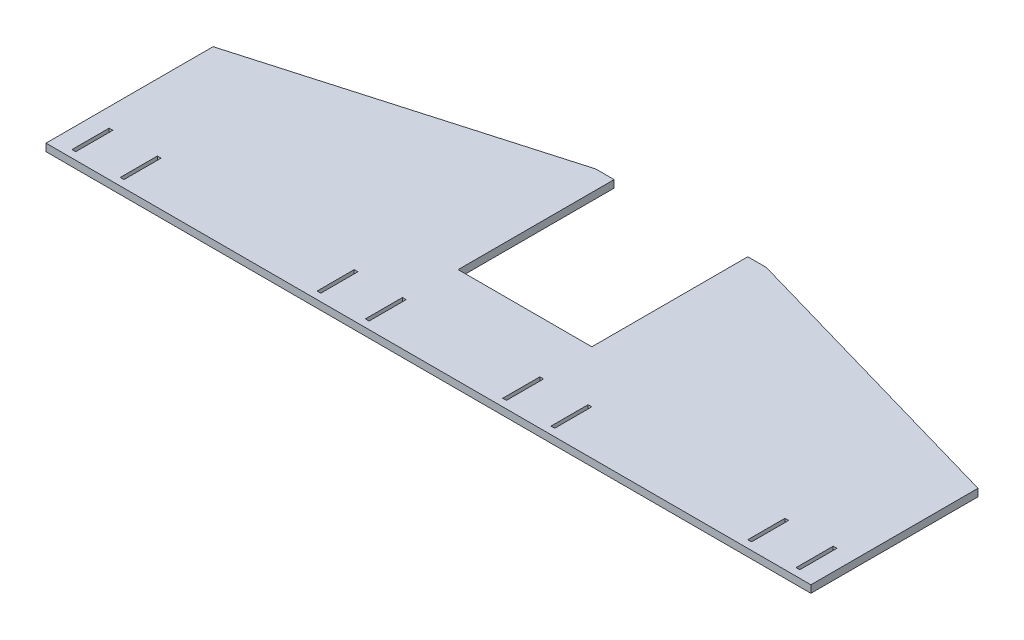
SolidWorks part; units mm, degrees
material "6061-T6 (SS)"
ref_plane "Front Plane" through (0, 0, 0) normal (0, 0, 1) x (1, 0, 0)
ref_plane "Top Plane" through (0, 0, 0) normal (0, 1, 0) x (1, 0, 0)
ref_plane "Right Plane" through (0, 0, 0) normal (1, 0, 0) x (0, 0, -1)
sketch "Sketch3" plane through (0, 0, 0) normal (0, 1, 0) x (1, 0, 0)
  line L0 (-103, 0) -> (-103, 45)
  line L2 (-18, 26) -> (-18, 68) construction
  line L4 (18, 68) -> (18, 26) construction
  line L6 (-103, 45) -> (-23, 68)
  line L7 (103, 45) -> (103, 0)
  line L8 (103, 0) -> (-103, 0)
  line L9 (-23, 68) -> (-18, 68)
  line L10 (-18, 68) -> (-18, 26)
  line L11 (-18, 26) -> (18, 26)
  line L12 (18, 26) -> (18, 68)
  line L13 (18, 68) -> (23, 68)
  line L14 (23, 68) -> (103, 45)
  point P2 (0, 0)
  dimension "D2" = 45
  dimension "D3" = 26
  dimension "D1" = 206
  dimension "D4" = 5
  dimension "D5" = 36
  dimension "D6" = 68
extrude "Boss-Extrude1" add sketch "Sketch3" along normal blind 2
sketch "Sketch4" plane through (0, 2, 0) normal (0, 1, 0) x (1, 0, 0)
  line L0 (-103, 45) -> (-103, 0) construction
  line L1 (-98, 12) -> (-97, 12)
  line L2 (-98, 12) -> (-98, 2)
  line L3 (-98, 2) -> (-97, 2)
  line L4 (-97, 12) -> (-97, 2)
  line L5 (-85, 12) -> (-84, 12)
  line L6 (-85, 12) -> (-85, 2)
  line L7 (-85, 2) -> (-84, 2)
  line L8 (-84, 12) -> (-84, 2)
  line L9 (-32, 12) -> (-31, 12)
  line L10 (-32, 12) -> (-32, 2)
  line L11 (-32, 2) -> (-31, 2)
  line L12 (-31, 12) -> (-31, 2)
  line L13 (-19, 12) -> (-18, 12)
  line L14 (-19, 12) -> (-19, 2)
  line L15 (-19, 2) -> (-18, 2)
  line L16 (-18, 12) -> (-18, 2)
  line L21 (-103, 0) -> (103, 0) construction
  line L22 (-18, 26) -> (-18, 68) construction
  dimension "D1" = 1
  dimension "D2" = 1
  dimension "D3" = 12
  dimension "D4" = 10
  dimension "D5" = 5
  dimension "D6" = 2
  dimension "D7" = 1
  dimension "D8" = 1
  dimension "D9" = 12
  dimension "D10" = 10
extrude "Cut-Extrude1" cut sketch "Sketch4" against normal through all
ref_plane "Plane1" through (0, 0, 0) normal (-1, 0, 0) x (0, 0, 1)
mirror "Mirror1" about plane through (0, 0, 0) normal (-1, 0, 0) of "Cut-Extrude1"
